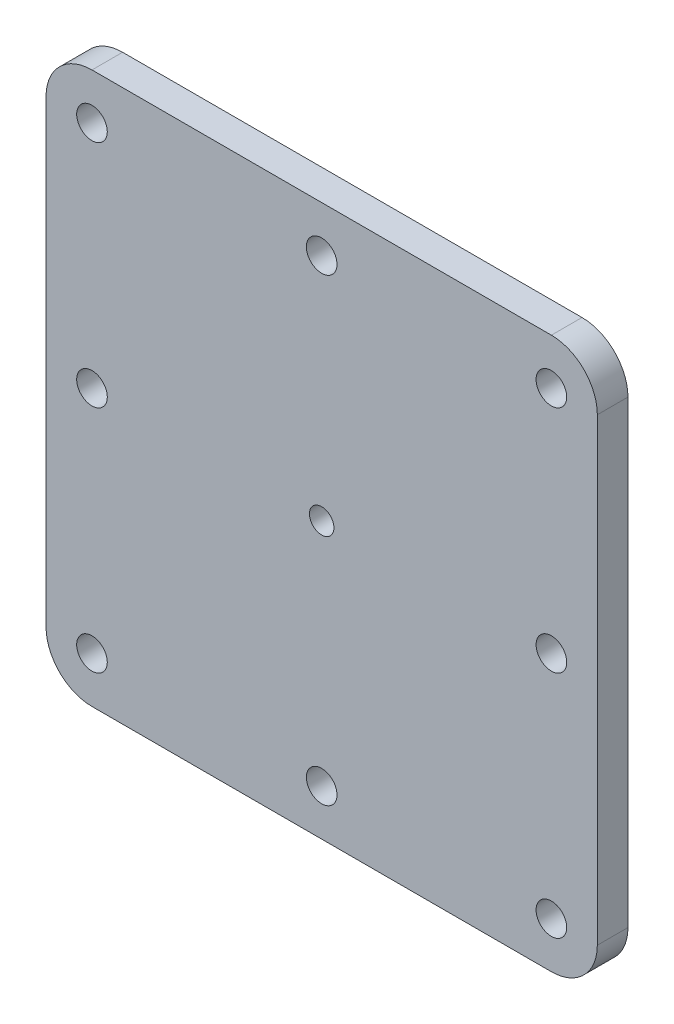
SolidWorks part; units mm, degrees
ref_plane "Front Plane" through (0, 0, 0) normal (0, 0, 1) x (1, 0, 0)
ref_plane "Top Plane" through (0, 0, 0) normal (0, 1, 0) x (1, 0, 0)
ref_plane "Right Plane" through (0, 0, 0) normal (1, 0, 0) x (0, 0, -1)
sketch "Sketch2" plane through (0, 0, 0) normal (0, 0, 1) x (1, 0, 0)
  line L0 (-75, 75) -> (75, 75) construction
  line L1 (-75, 90) -> (75, 90)
  line L2 (-90, 75) -> (-90, -75)
  line L3 (-75, -90) -> (75, -90)
  line L4 (90, 75) -> (90, -75)
  line L5 (-90, 90) -> (90, -90) construction
  line L6 (-90, -90) -> (90, 90) construction
  line L7 (75, 75) -> (75, -75) construction
  line L8 (75, -75) -> (-75, -75) construction
  line L9 (-75, -75) -> (-75, 75) construction
  line L15 (-60, 60) -> (60, -60) construction
  line L16 (-60, -60) -> (60, 60) construction
  arc A0 (-90, -75) -> (-75, -90) centre (-75, -75) ccw
  arc A1 (75, -90) -> (90, -75) centre (75, -75) ccw
  arc A2 (75, 90) -> (90, 75) centre (75, 75) cw
  arc A3 (-75, 90) -> (-90, 75) centre (-75, 75) ccw
  circle A4 centre (-75, 75) radius 5
  circle A5 centre (0, 75) radius 5
  circle A6 centre (75, 75) radius 5
  circle A7 centre (-75, 0) radius 5
  circle A8 centre (0, 0) radius 5 construction
  circle A9 centre (75, 0) radius 5
  circle A10 centre (-75, -75) radius 5
  circle A11 centre (0, -75) radius 5
  circle A12 centre (75, -75) radius 5
  point P0 (0, 0)
  dimension "D3" = 15
  dimension "D4" = 10
  dimension "D1" = 180
  dimension "D2" = 180
  dimension "D8" = 120
  dimension "D7" = 3
extrude "Boss-Extrude1" add sketch "Sketch2" along normal blind 10
sketch "Sketch3" plane through (0, 0, 10) normal (0, 0, 1) x (1, 0, 0)
  line L1 (-50, 50) -> (50, 50) construction
  line L2 (-50, 50) -> (-50, -50) construction
  line L3 (-50, -50) -> (50, -50) construction
  line L4 (50, 50) -> (50, -50) construction
  line L5 (-50, 50) -> (50, -50) construction
  line L6 (-50, -50) -> (50, 50) construction
  line L7 (0, 0) -> (-40, 0) construction
  line L8 (0, 0) -> (0, 40) construction
  line L9 (0, 40) -> (-40, 40) construction
  line L10 (-40, 0) -> (-40, 40) construction
  circle A0 centre (0, 0) radius 4
  point P0 (0, 0)
  dimension "D5" = 8
  dimension "D1" = 100
  dimension "D2" = 100
  dimension "D3" = 40
  dimension "D4" = 40
extrude "Cut-Extrude1" cut sketch "Sketch3" against normal blind 10
